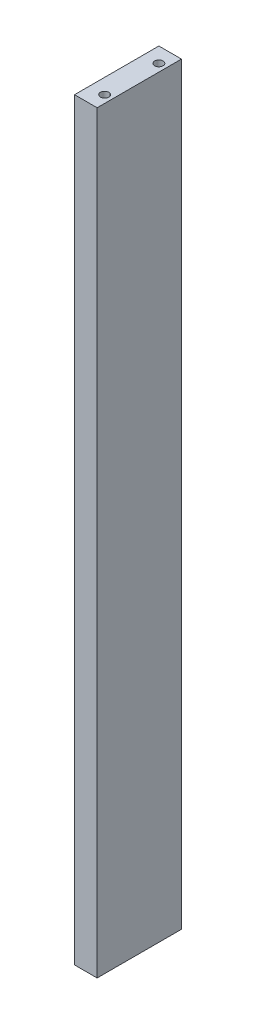
SolidWorks part; units mm, degrees
ref_plane "Front Plane" through (0, 0, 0) normal (0, 0, 1) x (1, 0, 0)
ref_plane "Top Plane" through (0, 0, 0) normal (0, 1, 0) x (1, 0, 0)
ref_plane "Right Plane" through (0, 0, 0) normal (1, 0, 0) x (0, 0, -1)
sketch "Sketch1" plane through (0, 0, 0) normal (0, 1, 0) x (1, 0, 0)
  line L1 (-3.75, -14) -> (3.75, -14)
  line L2 (-3.75, -14) -> (-3.75, 14)
  line L3 (-3.75, 14) -> (3.75, 14)
  line L4 (3.75, -14) -> (3.75, 14)
  line L5 (-3.75, -14) -> (3.75, 14) construction
  line L6 (-3.75, 14) -> (3.75, -14) construction
  circle A0 centre (1.25, -9) radius 1.4
  circle A1 centre (1.25, 9) radius 1.4
  point P0 (0, 0)
  point P10 (0, 0)
  point P11 (0, 0)
  dimension "D3" = 2.8
  dimension "D5" = 5
  dimension "D1" = 28
  dimension "D2" = 7.5
  dimension "D4" = 2.5
  dimension "D6" = 5
extrude "Boss-Extrude1" add sketch "Sketch1" along normal blind 250.2
sketch "Sketch3" plane through (-3.75, 0, 0) normal (-1, 0, 0) x (0, 0, 1)
  line L1 (-14, 250.2) -> (-14, 0) construction
  line L2 (-1.4762, 137.3663) -> (-3.5724, 125.7443)
  line L3 (1.4762, 137.3663) -> (3.5724, 125.7443)
  line L4 (-3.5724, 124.4557) -> (-1.4762, 112.8337)
  line L5 (3.5724, 124.4557) -> (1.4762, 112.8337)
  arc A0 (-3.5724, 125.7443) -> (-3.5724, 124.4557) centre (0, 125.1) ccw
  arc A1 (1.4762, 137.3663) -> (-1.4762, 137.3663) centre (0, 137.1) ccw
  arc A2 (-1.4762, 112.8337) -> (1.4762, 112.8337) centre (0, 113.1) ccw
  arc A3 (3.5724, 124.4557) -> (3.5724, 125.7443) centre (0, 125.1) ccw
  point P10 (-14, 125.1)
  dimension "D1" = 7.26
  dimension "D2" = 3
  dimension "D3" = 3
  dimension "D5" = 12
  dimension "D4" = 12
extrude "Cut-Extrude1" cut sketch "Sketch3" against normal blind 2
